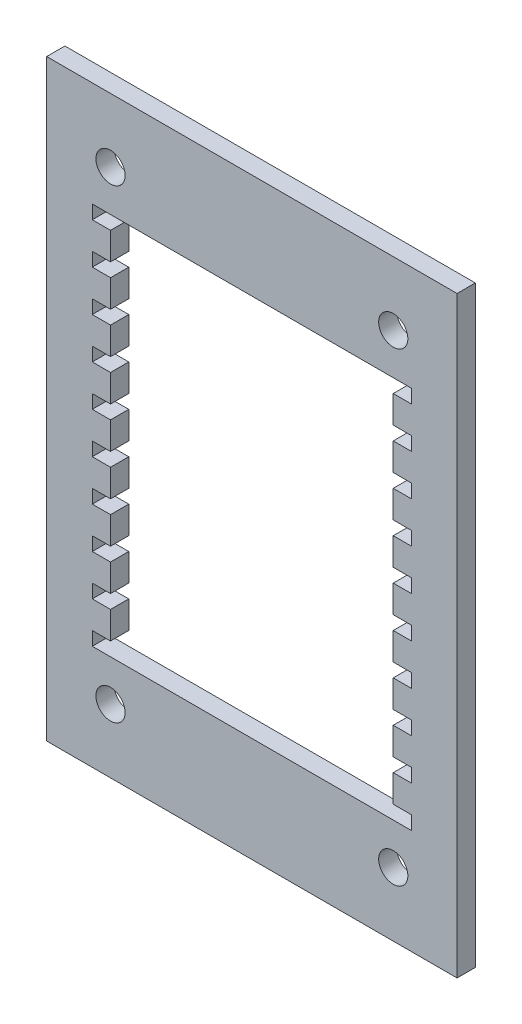
SolidWorks part; units mm, degrees
ref_plane "Ebene vorne" through (0, 0, 0) normal (0, 0, 1) x (1, 0, 0)
ref_plane "Ebene oben" through (0, 0, 0) normal (0, 1, 0) x (1, 0, 0)
ref_plane "Ebene rechts" through (0, 0, 0) normal (1, 0, 0) x (0, 0, -1)
sketch "Skizze1" plane through (0, 0, 0) normal (0, 0, 1) x (1, 0, 0)
  line L1 (0, 0) -> (45, 0)
  line L2 (0, 0) -> (0, 65)
  line L3 (0, 65) -> (45, 65)
  line L4 (45, 0) -> (45, 65)
  dimension "D1" = 45
  dimension "D2" = 65
extrude "Aufsatz-Linear austragen1" add sketch "Skizze1" along normal blind 2
sketch "Skizze3" plane through (0, 0, 2) normal (0, 0, 1) x (1, 0, 0)
  line L0 (45, 65) -> (0, 65) construction
  line L1 (5, 53.5) -> (40, 53.5)
  line L2 (5, 53.5) -> (5, 11.5)
  line L3 (5, 11.5) -> (40, 11.5)
  line L4 (40, 53.5) -> (40, 11.5)
  line L5 (0, 0) -> (45, 0) construction
  line L6 (45, 0) -> (45, 65) construction
  line L7 (0, 65) -> (0, 0) construction
  dimension "D1" = 11.5
  dimension "D2" = 11.5
  dimension "D3" = 5
  dimension "D4" = 5
extrude "Schnitt-Linear austragen1" cut sketch "Skizze3" against normal blind 2
sketch "Skizze4" plane through (5, 0, 0) normal (1, 0, 0) x (0, 0, -1)
  line L0 (-2, 53.5) -> (-2, 11.5) construction
  line L1 (-2, 52) -> (0, 52)
  line L2 (-2, 52) -> (-2, 49)
  line L3 (-2, 49) -> (0, 49)
  line L4 (0, 52) -> (0, 49)
  line L5 (0, 53.5) -> (0, 11.5) construction
  line L6 (0, 11.5) -> (-2, 11.5) construction
  line L7 (-2, 47.5) -> (0, 47.5)
  line L8 (-2, 47.5) -> (-2, 44.5)
  line L9 (-2, 44.5) -> (0, 44.5)
  line L10 (0, 47.5) -> (0, 44.5)
  line L11 (-2, 43) -> (0, 43)
  line L12 (-2, 43) -> (-2, 40)
  line L13 (-2, 40) -> (0, 40)
  line L14 (0, 43) -> (0, 40)
  line L15 (-2, 38.5) -> (0, 38.5)
  line L16 (-2, 38.5) -> (-2, 35.5)
  line L17 (-2, 35.5) -> (0, 35.5)
  line L18 (0, 38.5) -> (0, 35.5)
  line L23 (-2, 34) -> (0, 34)
  line L24 (-2, 34) -> (-2, 31)
  line L25 (-2, 31) -> (0, 31)
  line L26 (0, 34) -> (0, 31)
  line L27 (-2, 29.5) -> (0, 29.5)
  line L28 (-2, 29.5) -> (-2, 26.5)
  line L29 (-2, 26.5) -> (0, 26.5)
  line L30 (0, 29.5) -> (0, 26.5)
  line L31 (-2, 25) -> (0, 25)
  line L32 (-2, 25) -> (-2, 22)
  line L33 (-2, 22) -> (0, 22)
  line L34 (0, 25) -> (0, 22)
  line L35 (-2, 20.5) -> (0, 20.5)
  line L36 (-2, 20.5) -> (-2, 17.5)
  line L37 (-2, 17.5) -> (0, 17.5)
  line L38 (0, 20.5) -> (0, 17.5)
  line L39 (-2, 16) -> (0, 16)
  line L40 (-2, 16) -> (-2, 13)
  line L41 (-2, 13) -> (0, 13)
  line L42 (0, 16) -> (0, 13)
  line L44 (0, 53.5) -> (-2, 53.5) construction
  point P46 (0, 0)
  dimension "D1" = 1.5
  dimension "D2" = 3
  dimension "D3" = 1.5
  dimension "D4" = 3
  dimension "D5" = 1.5
  dimension "D6" = 3
  dimension "D7" = 1.5
  dimension "D8" = 3
  dimension "D9" = 1.5
  dimension "D10" = 3
  dimension "D11" = 1.5
  dimension "D12" = 3
  dimension "D13" = 1.5
  dimension "D14" = 3
  dimension "D15" = 1.5
  dimension "D16" = 3
  dimension "D17" = 1.5
  dimension "D18" = 3
  dimension "D19" = 2
  dimension "D20" = 1.5
extrude "Aufsatz-Linear austragen2" add sketch "Skizze4" along normal blind 2
sketch "Skizze5" plane through (40, 0, 0) normal (-1, 0, 0) x (0, 0, 1)
  line L0 (0, 11.5) -> (0, 53.5) construction
  line L1 (0, 52) -> (2, 52)
  line L2 (0, 52) -> (0, 49)
  line L3 (0, 49) -> (2, 49)
  line L4 (2, 52) -> (2, 49)
  line L5 (2, 11.5) -> (2, 53.5) construction
  line L6 (0, 11.5) -> (2, 11.5) construction
  line L7 (0, 47.5) -> (2, 47.5)
  line L8 (0, 47.5) -> (0, 44.5)
  line L9 (0, 44.5) -> (2, 44.5)
  line L10 (2, 47.5) -> (2, 44.5)
  line L11 (0, 43) -> (2, 43)
  line L12 (0, 43) -> (0, 40)
  line L13 (0, 40) -> (2, 40)
  line L14 (2, 43) -> (2, 40)
  line L15 (0, 38.5) -> (2, 38.5)
  line L16 (0, 38.5) -> (0, 35.5)
  line L17 (0, 35.5) -> (2, 35.5)
  line L18 (2, 38.5) -> (2, 35.5)
  line L19 (0, 34) -> (2, 34)
  line L20 (0, 34) -> (0, 31)
  line L21 (0, 31) -> (2, 31)
  line L22 (2, 34) -> (2, 31)
  line L23 (0, 29.5) -> (2, 29.5)
  line L24 (0, 29.5) -> (0, 26.5)
  line L25 (0, 26.5) -> (2, 26.5)
  line L26 (2, 29.5) -> (2, 26.5)
  line L27 (0, 25) -> (2, 25)
  line L28 (0, 25) -> (0, 22)
  line L29 (0, 22) -> (2, 22)
  line L30 (2, 25) -> (2, 22)
  line L31 (0, 20.5) -> (2, 20.5)
  line L32 (0, 20.5) -> (0, 17.5)
  line L33 (0, 17.5) -> (2, 17.5)
  line L34 (2, 20.5) -> (2, 17.5)
  line L35 (0, 16) -> (2, 16)
  line L36 (0, 16) -> (0, 13)
  line L37 (0, 13) -> (2, 13)
  line L38 (2, 16) -> (2, 13)
  dimension "D1" = 1.5
  dimension "D2" = 3
  dimension "D3" = 1.5
  dimension "D4" = 3
  dimension "D5" = 1.5
  dimension "D6" = 3
  dimension "D7" = 1.5
  dimension "D8" = 3
  dimension "D9" = 1.5
  dimension "D10" = 3
  dimension "D11" = 1.5
  dimension "D12" = 3
  dimension "D13" = 1.5
  dimension "D14" = 3
  dimension "D15" = 1.5
  dimension "D16" = 3
  dimension "D17" = 1.5
  dimension "D18" = 3
extrude "Aufsatz-Linear austragen3" add sketch "Skizze5" along normal blind 2
sketch "Skizze6" plane through (0, 0, 2) normal (0, 0, 1) x (1, 0, 0)
  line L0 (0, 65) -> (0, 0) construction
  line L1 (45, 65) -> (0, 65) construction
  line L2 (45, 0) -> (45, 65) construction
  line L3 (0, 0) -> (45, 0) construction
  circle A0 centre (7, 58) radius 1.6
  circle A1 centre (38, 58) radius 1.6
  circle A2 centre (38, 7) radius 1.6
  circle A3 centre (7, 7) radius 1.6
  point P10 (0, 0)
  dimension "D8" = 7
  dimension "D9" = 3.2
  dimension "D10" = 3.2
  dimension "D11" = 3.2
  dimension "D12" = 3.2
  dimension "D1" = 7
  dimension "D2" = 7
  dimension "D3" = 7
  dimension "D4" = 7
  dimension "D5" = 7
  dimension "D6" = 7
  dimension "D7" = 7
extrude "Schnitt-Linear austragen2" cut sketch "Skizze6" against normal blind 2
